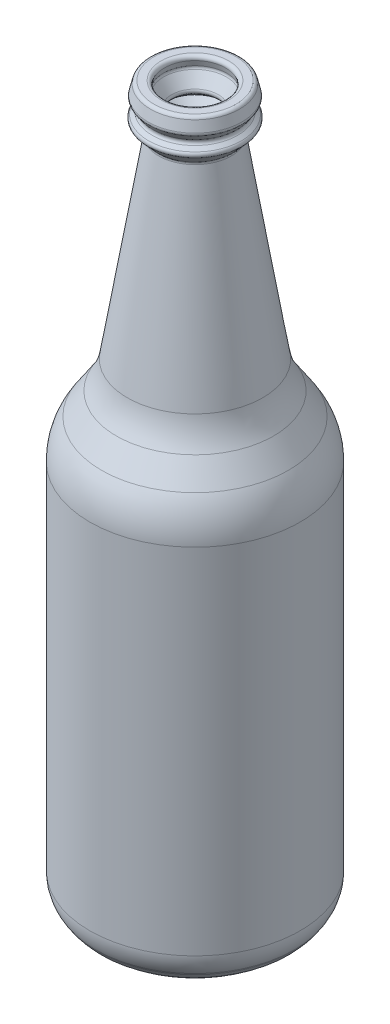
SolidWorks part; units mm, degrees
material "Brass"
ref_plane "Front Plane" through (0, 0, 0) normal (0, 0, 1) x (1, 0, 0)
ref_plane "Top Plane" through (0, 0, 0) normal (0, 1, 0) x (1, 0, 0)
ref_plane "Right Plane" through (0, 0, 0) normal (1, 0, 0) x (0, 0, -1)
sketch "Sketch1" plane through (0, 0, 0) normal (0, 0, 1) x (1, 0, 0)
  line L0 (0, 47.7867) -> (0, -175.6875) construction
  line L1 (12.5, 47.7867) -> (13.5, 43.7867)
  line L2 (13.5, 43.7867) -> (11.5, 40.9056)
  line L3 (11.5, 40.9056) -> (14, 38.7867)
  line L4 (14, 38.7867) -> (10.2828, 34.7867)
  line L5 (10.2828, 34.7867) -> (20, -25.2133)
  line L6 (20, -25.2133) -> (30, -40.2133)
  line L7 (25, -157.7133) -> (30, -150.2133)
  line L8 (25, -157.7133) -> (0, -157.7133)
  line L9 (0, 47.7867) -> (12.5, 47.7867)
  line L10 (30, -40.2133) -> (30, -150.2133)
  line L11 (0, 47.7867) -> (0, -157.7133)
  point P9 (1.2203, 35.4861)
  point P10 (1.2203, 35.3171)
  point P14 (7.5647, 35.0917)
  point P15 (0, -118.0189)
  point P16 (0, -175.6875)
  point P18 (0, 0)
  point P19 (11.5, 43.3027)
  point P20 (11.5, 40.9056)
  point P21 (9.2873, 34.654)
  point P22 (10.2828, 34.7867)
  dimension "D1" = 13
  dimension "D2" = 12.5
  dimension "D3" = 9
  dimension "D4" = 4
  dimension "D5" = 13.5
  dimension "D6" = 14
  dimension "D7" = 11.5
  dimension "D8" = 60
  dimension "D9" = 20
  dimension "D10" = 15
  dimension "D11" = 30
  dimension "D12" = 7.5
  dimension "D13" = 110
  dimension "D14" = 25
revolve "Revolve1" add sketch "Sketch1" angle 360 about L0
shell "Shell1" thickness 4
fillet "Fillet1" radius 20 2 edges at (0, -25.2133, 20) (0, -40.2133, 30)
fillet "Fillet2" radius 10 2 edges at (0, -150.2133, 30) (0, -157.7133, 25)
fillet "Fillet3" radius 1 9 edges at (0, 36.0774, 6.0217) (0, 40.2026, 6.1428) (0, 44.577, 9.1793) (0, 47.7867, -8.3769) (0, 47.7867, 12.5) (0, 43.7867, 13.5) (0, 40.9056, 11.5) (0, 38.7867, 14) (0, 34.7867, 10.2828)
